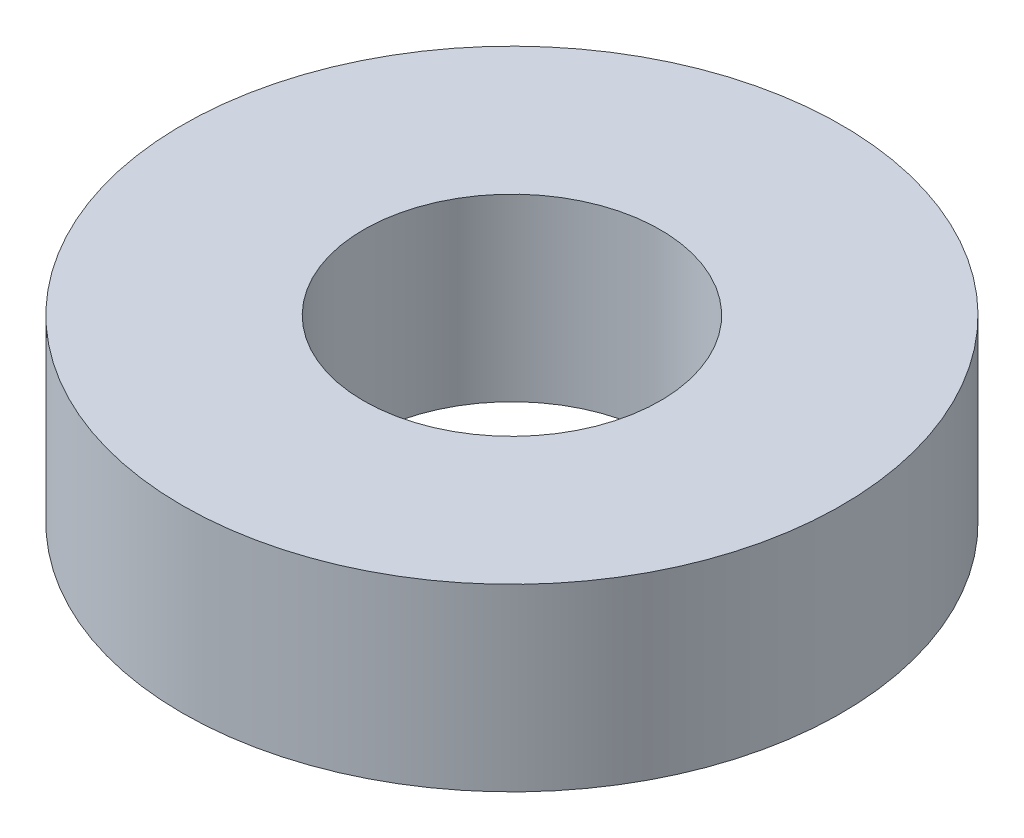
SolidWorks part; units mm, degrees
ref_plane "Plan de face" through (0, 0, 0) normal (0, 0, 1) x (1, 0, 0)
ref_plane "Plan de dessus" through (0, 0, 0) normal (0, 1, 0) x (1, 0, 0)
ref_plane "Plan de droite" through (0, 0, 0) normal (1, 0, 0) x (0, 0, -1)
sketch "Esquisse1" plane through (0, 0, 0) normal (0, 1, 0) x (1, 0, 0)
  circle A0 centre (0, 0) radius 4.95
  circle A1 centre (0, 0) radius 11
  dimension "D1" = 9.9
  dimension "D2" = 22
extrude "Boss.-Extru.1" add sketch "Esquisse1" along normal blind 6
